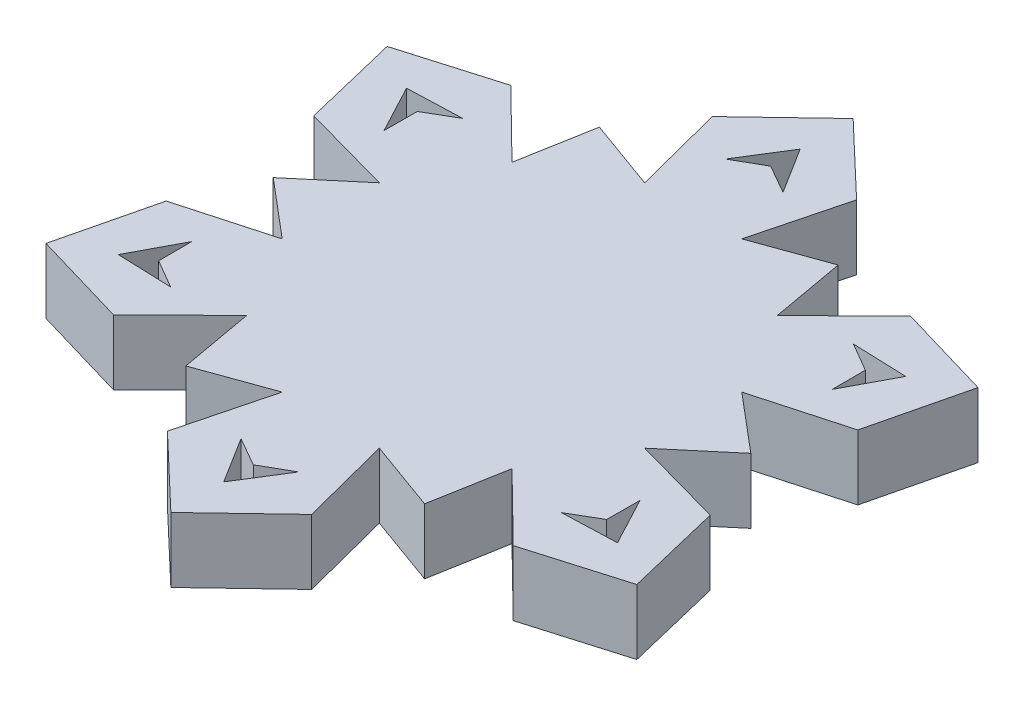
SolidWorks part; units mm, degrees
ref_plane "Front Plane" through (0, 0, 0) normal (0, 0, 1) x (1, 0, 0)
ref_plane "Top Plane" through (0, 0, 0) normal (0, 1, 0) x (1, 0, 0)
ref_plane "Right Plane" through (0, 0, 0) normal (1, 0, 0) x (0, 0, -1)
sketch "Sketch1" plane through (0, 0, 0) normal (0, 1, 0) x (1, 0, 0)
  line L0 (0, 0) -> (12.941, 48.2963) construction
  line L1 (0, 0) -> (25, 43.3013) construction
  line L2 (0, -55) -> (0, 55) construction
  line L3 (7.1175, 26.563) -> (17.5, 30.3109)
  line L4 (10.5689, 39.9348) -> (7.1175, 26.563)
  line L5 (0, 50) -> (10.5689, 39.9348)
  line L6 (0, 42.2413) -> (4.2196, 35.4988)
  line L7 (4.2196, 35.4988) -> (0, 37.9113)
  line L8 (28.633, 21.4037) -> (32.8321, 18.9556)
  line L9 (19.4454, 19.4454) -> (17.5, 30.3109)
  line L10 (29.3001, 29.1204) -> (19.4454, 19.4454)
  line L11 (36.5821, 21.1207) -> (28.633, 21.4037)
  line L12 (43.3013, 25) -> (29.3001, 29.1204)
  line L13 (43.3013, 25) -> (39.8691, 10.8144)
  line L14 (36.5821, 21.1207) -> (32.8527, 14.0951)
  line L15 (32.8527, 14.0951) -> (32.8321, 18.9556)
  line L16 (39.8691, 10.8144) -> (26.563, 7.1175)
  line L17 (26.563, 7.1175) -> (35, 0)
  line L18 (26.563, -7.1175) -> (35, 0)
  line L19 (39.8691, -10.8144) -> (26.563, -7.1175)
  line L20 (43.3013, -25) -> (39.8691, -10.8144)
  line L21 (36.5821, -21.1207) -> (32.8527, -14.0951)
  line L22 (32.8527, -14.0951) -> (32.8321, -18.9556)
  line L23 (43.3013, -25) -> (29.3001, -29.1204)
  line L24 (36.5821, -21.1207) -> (28.633, -21.4037)
  line L25 (28.633, -21.4037) -> (32.8321, -18.9556)
  line L26 (29.3001, -29.1204) -> (19.4454, -19.4454)
  line L27 (19.4454, -19.4454) -> (17.5, -30.3109)
  line L28 (7.1175, -26.563) -> (17.5, -30.3109)
  line L29 (10.5689, -39.9348) -> (7.1175, -26.563)
  line L30 (0, -50) -> (10.5689, -39.9348)
  line L31 (0, -42.2413) -> (4.2196, -35.4988)
  line L32 (4.2196, -35.4988) -> (0, -37.9113)
  line L33 (0, -50) -> (-10.5689, -39.9348)
  line L34 (0, -42.2413) -> (-4.2196, -35.4988)
  line L35 (-4.2196, -35.4988) -> (0, -37.9113)
  line L36 (-10.5689, -39.9348) -> (-7.1175, -26.563)
  line L37 (-7.1175, -26.563) -> (-17.5, -30.3109)
  line L38 (-19.4454, -19.4454) -> (-17.5, -30.3109)
  line L39 (-29.3001, -29.1204) -> (-19.4454, -19.4454)
  line L40 (-43.3013, -25) -> (-29.3001, -29.1204)
  line L41 (-36.5821, -21.1207) -> (-28.633, -21.4037)
  line L42 (-28.633, -21.4037) -> (-32.8321, -18.9556)
  line L43 (-43.3013, -25) -> (-39.8691, -10.8144)
  line L44 (-36.5821, -21.1207) -> (-32.8527, -14.0951)
  line L45 (-32.8527, -14.0951) -> (-32.8321, -18.9556)
  line L46 (-39.8691, -10.8144) -> (-26.563, -7.1175)
  line L47 (-26.563, -7.1175) -> (-35, 0)
  line L48 (-26.563, 7.1175) -> (-35, 0)
  line L49 (-39.8691, 10.8144) -> (-26.563, 7.1175)
  line L50 (-43.3013, 25) -> (-39.8691, 10.8144)
  line L51 (-36.5821, 21.1207) -> (-32.8527, 14.0951)
  line L52 (-32.8527, 14.0951) -> (-32.8321, 18.9556)
  line L53 (-43.3013, 25) -> (-29.3001, 29.1204)
  line L54 (-36.5821, 21.1207) -> (-28.633, 21.4037)
  line L55 (-28.633, 21.4037) -> (-32.8321, 18.9556)
  line L56 (-29.3001, 29.1204) -> (-19.4454, 19.4454)
  line L57 (-19.4454, 19.4454) -> (-17.5, 30.3109)
  line L58 (-7.1175, 26.563) -> (-17.5, 30.3109)
  line L59 (-10.5689, 39.9348) -> (-7.1175, 26.563)
  line L60 (0, 50) -> (-10.5689, 39.9348)
  line L61 (0, 42.2413) -> (-4.2196, 35.4988)
  line L62 (-4.2196, 35.4988) -> (0, 37.9113)
  circle A0 centre (0, 0) radius 50 construction
  circle A1 centre (0, 0) radius 35 construction
  circle A2 centre (0, 0) radius 27.5 construction
  point P90 (0, 0)
  dimension "D1" = 70
  dimension "D2" = 100
  dimension "D3" = 55
  dimension "D4" = 30
  dimension "D5" = 15
  dimension "D6" = 6
extrude "Boss-Extrude1" add sketch "Sketch1" along normal blind 9.525 contours L5 L60 L59 L58 L57 L56 L53 L50 L49 L48 L47 L46 L43 L40 L39 L38 L37 L36 L33 L30 L29 L28 L27 L26 L23 L20 L19 L18 L17 L16 L13 L12 L10 L9 L3 L4 L62 L61 L6 L7 L54 L55 L52 L51 L44 L45 L42 L41
